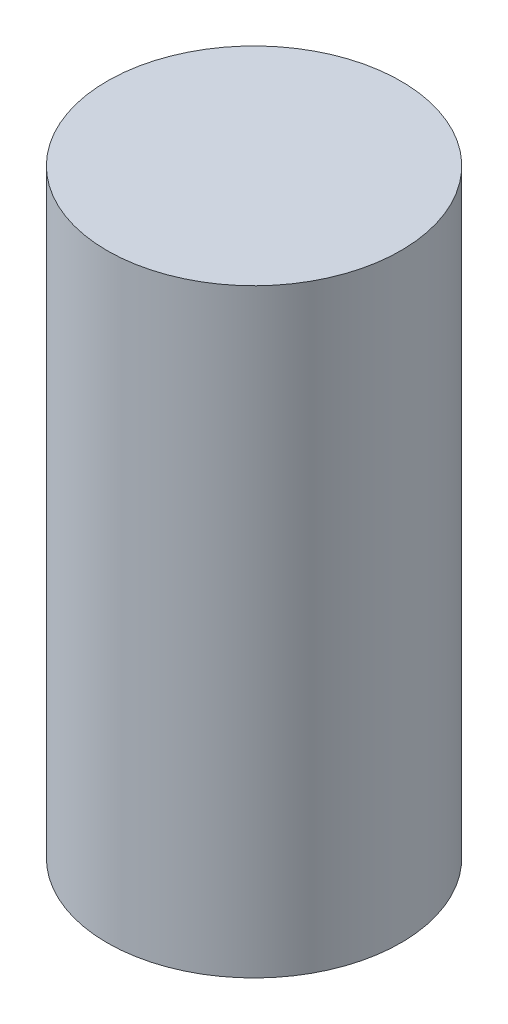
SolidWorks part; units mm, degrees
ref_plane "Front Plane" through (0, 0, 0) normal (0, 0, 1) x (1, 0, 0)
ref_plane "Top Plane" through (0, 0, 0) normal (0, 1, 0) x (1, 0, 0)
ref_plane "Right Plane" through (0, 0, 0) normal (1, 0, 0) x (0, 0, -1)
sketch "Sketch1" plane through (0, 0, 0) normal (0, 1, 0) x (1, 0, 0)
  circle A0 centre (0, 0) radius 4.9
  dimension "D1" = 9.8
extrude "Boss-Extrude1" add sketch "Sketch1" along normal blind 20
